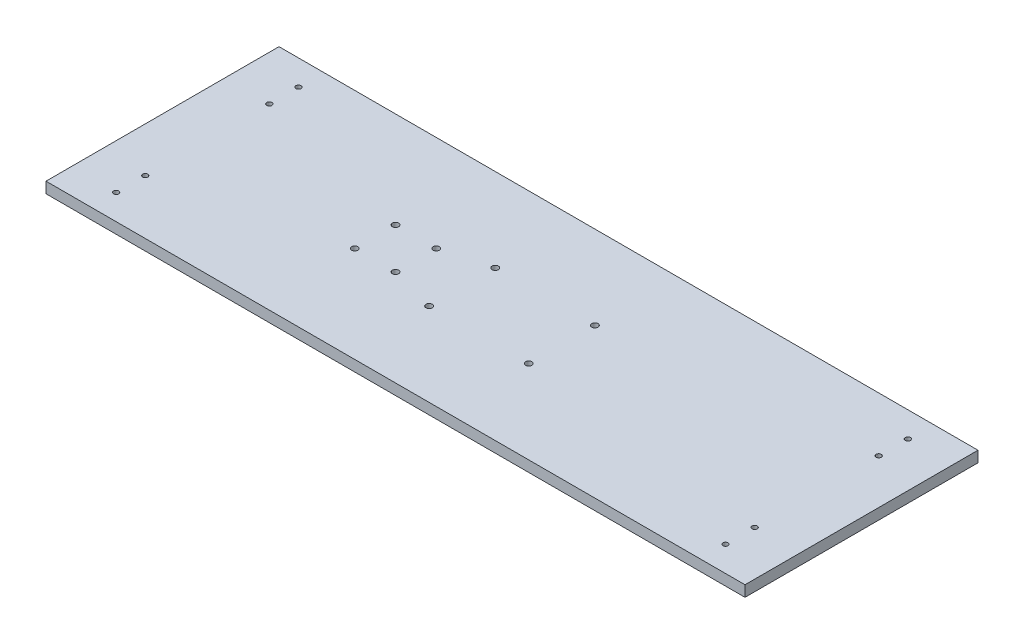
SolidWorks part; units mm, degrees
material "Pine"
ref_plane "Front Plane" through (0, 0, 0) normal (0, 0, 1) x (1, 0, 0)
ref_plane "Top Plane" through (0, 0, 0) normal (0, 1, 0) x (1, 0, 0)
ref_plane "Right Plane" through (0, 0, 0) normal (1, 0, 0) x (0, 0, -1)
sketch "Sketch1" plane through (0, 0, 0) normal (0, 1, 0) x (1, 0, 0)
  line L1 (0, 0) -> (609.6, 0)
  line L2 (0, 0) -> (0, 203.2)
  line L3 (0, 203.2) -> (609.6, 203.2)
  line L4 (609.6, 0) -> (609.6, 203.2)
  line L5 (304.8, 203.2) -> (304.8, 0) construction
  line L6 (0, 101.6) -> (609.6, 101.6) construction
  point P124 (304.8, 101.6)
  dimension "D1" = 609.6
  dimension "D2" = 203.2
extrude "Table Blank" add sketch "Sketch1" along normal blind 9.525
sketch "Table Location" plane through (0, 9.525, 0) normal (0, 1, 0) x (1, 0, 0)
  line L0 (0, 101.6) -> (609.6, 101.6) construction
  line L1 (228.6, 152.4) -> (381, 152.4) construction
  line L2 (228.6, 152.4) -> (228.6, 50.8) construction
  line L3 (228.6, 50.8) -> (381, 50.8) construction
  line L4 (381, 152.4) -> (381, 50.8) construction
  line L5 (304.8, 50.8) -> (304.8, 152.4) construction
  line L6 (228.6, 101.6) -> (381, 101.6) construction
  line L7 (304.8, 203.2) -> (304.8, 0) construction
  line L9 (261.366, 130.429) -> (348.234, 130.429) construction
  line L10 (261.366, 130.429) -> (261.366, 72.771) construction
  line L11 (261.366, 72.771) -> (348.234, 72.771) construction
  line L12 (348.234, 130.429) -> (348.234, 72.771) construction
  line L13 (304.8, 72.771) -> (304.8, 130.429) construction
  line L14 (261.366, 101.6) -> (348.234, 101.6) construction
  circle A0 centre (261.366, 72.771) radius 2.5 construction
  circle A1 centre (261.366, 130.429) radius 2.5 construction
  circle A2 centre (348.234, 130.429) radius 2.5 construction
  circle A3 centre (348.234, 72.771) radius 2.5 construction
  point P124 (304.8, 101.6)
  point P224 (304.8, 101.6)
  dimension "D5" = 5
  dimension "D1" = 152.4
  dimension "D2" = 101.6
  dimension "D3" = 86.868
  dimension "D4" = 57.658
hole_wizard "Table Holes (M5 Clearance)" positions "Sketch4" profile "Sketch5" hole size "M5" standard "ANSI Metric" end condition through all
sketch "Sketch4" plane through (0, 9.525, 0) normal (0, 1, 0) x (1, 0, 0)
  point P0 (261.366, 130.429)
  point P3 (348.234, 130.429)
  point P6 (348.234, 72.771)
  point P9 (261.366, 72.771)
sketch "Sketch5" plane through (261.366, 9.525, -130.429) normal (1, 0, 0) x (0, 0, 1)
  line L0 (0, 0) -> (0, 9.525)
  line L1 (0, 9.525) -> (2.75, 9.525)
  line L2 (2.75, 9.525) -> (2.75, 0)
  line L5 (2.75, 0) -> (0, 0)
  line L11 (0, -6.35) -> (0, 107.95) construction
  dimension "Thru Hole Dia." = 5.5
  dimension "Thru Hole Depth" = 9.525
sketch "Runner Location" plane through (0, 9.525, 0) normal (0, 1, 0) x (1, 0, 0)
  line L0 (0, 101.6) -> (609.6, 101.6) construction
  line L1 (177.8, 127) -> (228.6, 127) construction
  line L2 (177.8, 127) -> (177.8, 76.2) construction
  line L3 (177.8, 76.2) -> (228.6, 76.2) construction
  line L4 (228.6, 127) -> (228.6, 76.2) construction
  line L5 (203.2, 76.2) -> (203.2, 127) construction
  line L6 (177.8, 101.6) -> (228.6, 101.6) construction
  line L7 (228.6, 152.4) -> (228.6, 50.8) construction
  line L8 (185.42, 119.38) -> (185.42, 83.82) construction
  line L9 (185.42, 83.82) -> (220.98, 83.82) construction
  line L10 (220.98, 119.38) -> (220.98, 83.82) construction
  line L11 (185.42, 119.38) -> (220.98, 119.38) construction
  point P136 (203.2, 101.6)
  dimension "D1" = 50.8
  dimension "D2" = 7.62
hole_wizard "Runner Holes" positions "Sketch7" profile "Sketch8" hole size "M5" standard "ANSI Metric" end condition through all
sketch "Sketch7" plane through (0, 9.525, 0) normal (0, 1, 0) x (1, 0, 0)
  point P0 (185.42, 119.38)
  point P3 (220.98, 119.38)
  point P6 (220.98, 83.82)
  point P9 (185.42, 83.82)
sketch "Sketch8" plane through (185.42, 9.525, -119.38) normal (1, 0, 0) x (0, 0, 1)
  line L0 (0, 0) -> (0, 9.525)
  line L1 (0, 9.525) -> (2.75, 9.525)
  line L2 (2.75, 9.525) -> (2.75, 0)
  line L5 (2.75, 0) -> (0, 0)
  line L11 (0, -6.35) -> (0, 107.95) construction
  dimension "Thru Hole Dia." = 5.5
  dimension "Thru Hole Depth" = 9.525
sketch "Wheel Location" plane through (0, 9.525, 0) normal (0, 1, 0) x (1, 0, 0)
  line L0 (55.88, 187.452) -> (55.88, 15.748) construction
  line L1 (0, 101.6) -> (609.6, 101.6) construction
  line L2 (0, 0) -> (0, 203.2) construction
  line L3 (30.1879, 187.452) -> (45.4279, 187.452) construction
  line L4 (25.6921, 187.452) -> (30.1879, 187.452) construction
  line L5 (25.6921, 187.452) -> (25.6921, 15.748) construction
  line L6 (25.6921, 15.748) -> (30.1879, 15.748) construction
  line L7 (30.1879, 187.452) -> (30.1879, 15.748) construction
  line L8 (27.94, 15.748) -> (27.94, 187.452) construction
  line L9 (25.6921, 101.6) -> (30.1879, 101.6) construction
  line L10 (30.1879, 15.748) -> (45.4279, 15.748) construction
  line L11 (30.1879, 15.748) -> (30.1879, 53.848) construction
  line L12 (30.1879, 53.848) -> (45.4279, 53.848) construction
  line L13 (45.4279, 15.748) -> (45.4279, 53.848) construction
  line L14 (45.4279, 187.452) -> (45.4279, 149.352) construction
  line L15 (30.1879, 149.352) -> (45.4279, 149.352) construction
  point P2 (55.88, 101.6)
  point P11 (39.0779, 22.098)
  point P16 (39.0779, 47.498)
  point P17 (39.0779, 181.102)
  point P18 (39.0779, 155.702)
  point P487 (27.94, 101.6)
  dimension "D1" = 171.704
  dimension "D2" = 55.88
  dimension "D3" = 4.4958
  dimension "D4" = 27.94
  dimension "D5" = 6.35
  dimension "D7" = 15.24
  dimension "D8" = 38.1
  dimension "D6" = 6.35
  dimension "D9" = 25.4
hole_wizard "Wheel Holes (M4 Clearance)" positions "Sketch10" profile "Sketch11" hole size "M4" standard "ANSI Metric" end condition through all
sketch "Sketch10" plane through (0, 9.525, 0) normal (0, 1, 0) x (1, 0, 0)
  point P0 (39.0779, 181.102)
  point P3 (39.0779, 155.702)
  point P6 (39.0779, 47.498)
  point P9 (39.0779, 22.098)
sketch "Sketch11" plane through (39.0779, 9.525, -181.102) normal (1, 0, 0) x (0, 0, 1)
  line L0 (0, 0) -> (0, 9.525)
  line L1 (0, 9.525) -> (2.25, 9.525)
  line L2 (2.25, 9.525) -> (2.25, 0)
  line L5 (2.25, 0) -> (0, 0)
  line L11 (0, -6.35) -> (0, 107.95) construction
  dimension "Thru Hole Dia." = 4.5
  dimension "Thru Hole Depth" = 9.525
ref_plane "Plane1" through (304.8, 0, 0) normal (-1, 0, 0) x (0, 0, 1)
mirror "Mirror1" about plane through (304.8, 0, 0) normal (-1, 0, 0) of "Wheel Holes (M4 Clearance)"
equation "\"baseplate x\"= 24"
equation "\"baseplate y\"= 8"
equation "\"D1@Sketch1\"=\"baseplate x\""
equation "\"D2@Sketch1\"=\"baseplate y\""
equation "\"stock thick\"= 3 / 8"
equation "\"D1@Table Blank\" = \"stock thick\""
equation "\"table x\"= 6"
equation "\"table y\"= 4"
equation "\"D1@Table Location\" = \"table x\""
equation "\"D2@Table Location\" = \"table y\""
equation "\"width wheelmount\"= 6.76"
equation "\"offset wheelmount\"= 2.2"
equation "\"D2@Wheel Location\" = \"offset wheelmount\""
equation "\"D1@Wheel Location\" = \"width wheelmount\""
equation "\"D4@Wheel Location\" = \"D2@Wheel Location\" / 2"
